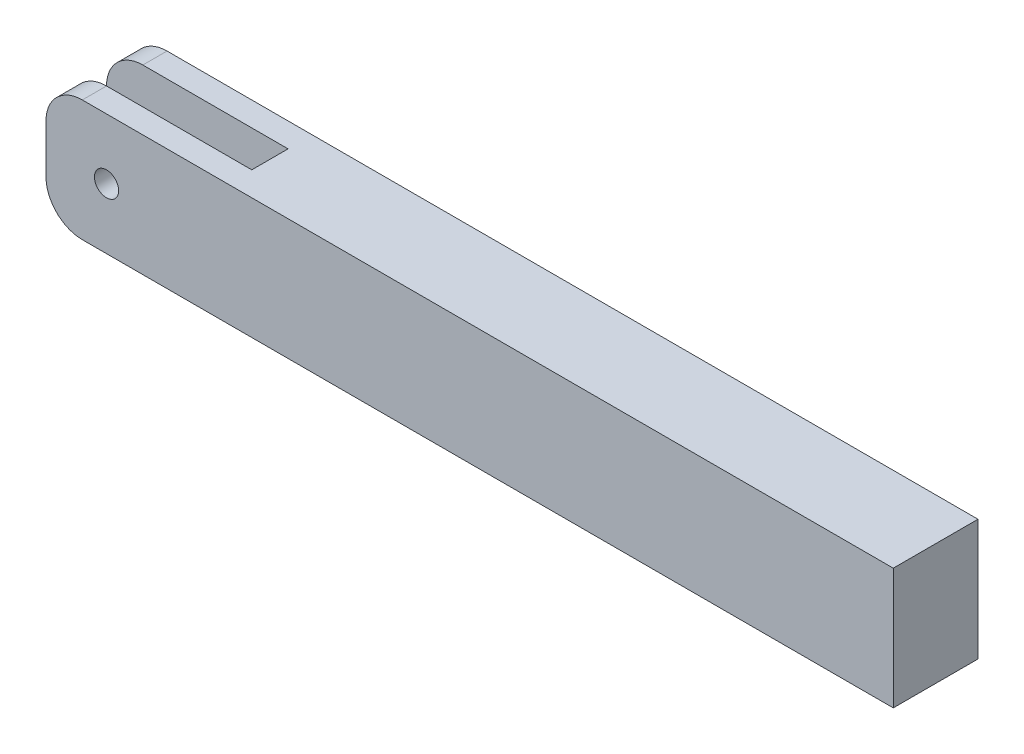
SolidWorks part; units mm, degrees
ref_plane "Front" through (0, 0, 0) normal (0, 0, 1) x (1, 0, 0)
ref_plane "Top" through (0, 0, 0) normal (0, 1, 0) x (1, 0, 0)
ref_plane "Right" through (0, 0, 0) normal (1, 0, 0) x (0, 0, -1)
sketch "Sketch1" plane through (0, 0, 0) normal (0, 0, 1) x (1, 0, 0)
  line L1 (-10, 25) -> (325, 25)
  line L2 (-25, 10) -> (-25, -10)
  line L3 (-10, -25) -> (325, -25)
  line L4 (325, 25) -> (325, -25)
  arc A1 (-10, -25) -> (-25, -10) centre (-10, -10) cw
  arc A2 (-10, 25) -> (-25, 10) centre (-10, 10) ccw
  dimension "D6" = 15
  dimension "D1" = 50
  dimension "D2" = 350
  dimension "D3" = 25
  dimension "D4" = 25
extrude "Extrude1" add sketch "Sketch1" along normal mid plane 35
sketch "Sketch2" plane through (0, 25, 0) normal (0, 1, 0) x (-1, 0, 0)
  line L0 (25, 17.5) -> (25, -17.5) construction
  line L1 (25, -7.5) -> (-50, -7.5)
  line L2 (25, -7.5) -> (25, 7.5)
  line L3 (25, 7.5) -> (-50, 7.5)
  line L4 (-50, -7.5) -> (-50, 7.5)
  point P6 (25, 0)
  dimension "D1" = 75
  dimension "D2" = 15
extrude "Cut-Extrude1" cut sketch "Sketch2" against normal through all
sketch "Sketch3" plane through (0, 0, 0) normal (0, 0, 1) x (1, 0, 0)
  circle A0 centre (0, 0) radius 5
  dimension "D1" = 10
extrude "Cut-Extrude2" cut sketch "Sketch3" against normal through all and the other way through all
